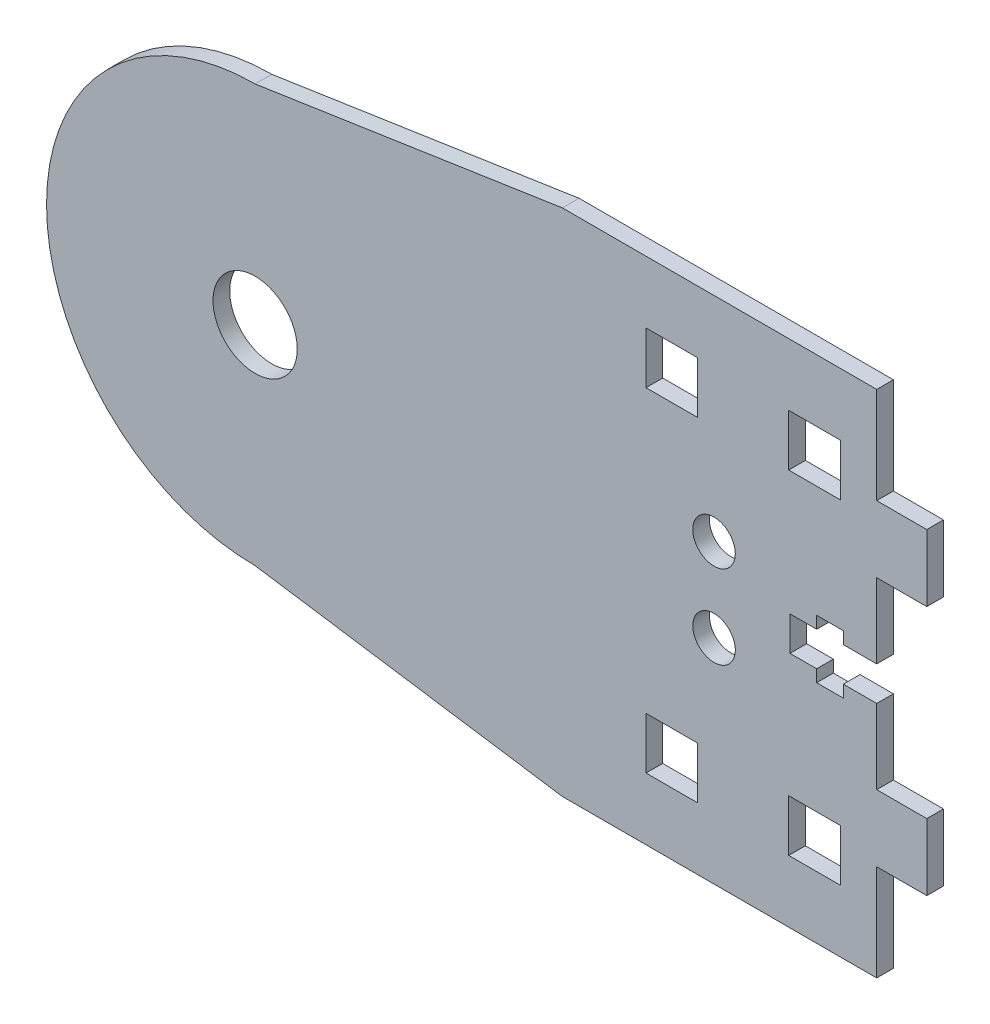
SolidWorks part; units mm, degrees
ref_plane "前视基准面" through (0, 0, 0) normal (0, 0, 1) x (1, 0, 0)
ref_plane "上视基准面" through (0, 0, 0) normal (0, 1, 0) x (1, 0, 0)
ref_plane "右视基准面" through (0, 0, 0) normal (1, 0, 0) x (0, 0, -1)
sketch "草图1" plane through (0, 0, 0) normal (0, 0, 1) x (1, 0, 0)
  line L0 (0, 0) -> (118.4069, 0) construction
  line L8 (58.5, -5) -> (58.5, -19.6678) construction
  line L9 (63.95, -16.9) -> (63.95, -23.1)
  line L10 (46.85, -16.9) -> (53.05, -16.9)
  line L11 (46.85, -16.9) -> (46.85, -23.1)
  line L12 (46.85, -23.1) -> (53.05, -23.1)
  line L13 (53.05, -16.9) -> (53.05, -23.1)
  line L14 (46.85, -16.9) -> (53.05, -23.1) construction
  line L15 (46.85, -23.1) -> (53.05, -16.9) construction
  line L16 (70.15, -23.1) -> (63.95, -23.1)
  line L17 (70.15, -16.9) -> (70.15, -23.1)
  line L18 (70.15, -16.9) -> (63.95, -16.9)
  line L19 (53.05, 16.9) -> (53.05, 23.1)
  line L20 (46.85, 23.1) -> (53.05, 23.1)
  line L21 (46.85, 16.9) -> (53.05, 16.9)
  line L22 (46.85, 16.9) -> (46.85, 23.1)
  line L23 (63.95, 16.9) -> (63.95, 23.1)
  line L24 (70.15, 23.1) -> (63.95, 23.1)
  line L25 (70.15, 16.9) -> (70.15, 23.1)
  line L26 (70.15, 16.9) -> (63.95, 16.9)
  line L27 (0, -25) -> (36.8229, -30.548)
  line L30 (0, 25) -> (36.8229, 30.548)
  line L32 (55, -5) -> (55, 5) construction
  line L33 (70.5, 2.05) -> (70.5, 3.5)
  line L40 (36.8229, 30.548) -> (74.5, 30.548)
  line L41 (74.5, -30.548) -> (36.8229, -30.548)
  line L54 (74.5, 2.05) -> (70.5, 2.05)
  line L55 (70.5, 3.5) -> (67.3, 3.5)
  line L56 (67.3, 3.5) -> (67.3, 2.05)
  line L57 (67.3, 2.05) -> (64.1, 2.05)
  line L58 (64.1, 2.05) -> (64.1, -2.05)
  line L59 (74.5, 30.548) -> (74.5, 2.05) construction
  line L60 (74.5, 19) -> (80.5, 19)
  line L61 (80.5, 19) -> (80.5, 11)
  line L62 (80.5, 11) -> (74.5, 11)
  line L63 (80.5, 15) -> (74.5, 15) construction
  line L64 (74.5, 11) -> (74.5, 2.05)
  line L65 (74.5, 19) -> (74.5, 30.548)
  line L66 (67.3, -2.05) -> (64.1, -2.05)
  line L67 (67.3, -3.5) -> (67.3, -2.05)
  line L68 (70.5, -3.5) -> (67.3, -3.5)
  line L69 (74.5, -2.05) -> (70.5, -2.05)
  line L70 (70.5, -2.05) -> (70.5, -3.5)
  line L71 (80.5, -15) -> (74.5, -15) construction
  line L72 (74.5, -11) -> (74.5, -2.05)
  line L73 (80.5, -11) -> (74.5, -11)
  line L74 (80.5, -19) -> (80.5, -11)
  line L75 (74.5, -19) -> (80.5, -19)
  line L76 (74.5, -19) -> (74.5, -30.548)
  circle A0 centre (0, 0) radius 5.05
  circle A1 centre (55, 5) radius 2.55
  circle A5 centre (55, -5) radius 2.55
  circle A6 centre (0, 0) radius 25 construction
  arc A7 (0, 25) -> (0, -25) centre (0, 0) ccw
  circle A8 centre (0, 0) radius 40 construction
  point P10 (49.95, -20)
  point P22 (67.05, -20)
  point P31 (67.05, 20)
  point P52 (64.1, 0)
  dimension "D1" = 10.1
  dimension "D5" = 55
  dimension "D6" = 6.2
  dimension "D9" = 80
  dimension "D10" = 3.5
  dimension "D11" = 2.05
  dimension "D2" = 5
  dimension "D3" = 3.5
  dimension "D4" = 6.2
  dimension "D7" = 17.1
  dimension "D8" = 3.2
  dimension "D12" = 4
  dimension "D13" = 74.5
  dimension "D14" = 15
  dimension "D15" = 8
  dimension "D16" = 6
extrude "凸台-拉伸1" add sketch "草图1" along normal blind 2
sketch "草图2" plane through (74.5, 0, 0) normal (1, 0, 0) x (0, 0, -1)
  line L0 (-1, -2.05) -> (-1, 2.05) construction
  line L1 (-2, -2.05) -> (0, -2.05) construction
  line L2 (-2, 2.05) -> (0, 2.05) construction
  circle A0 centre (-1, 0) radius 2.05
